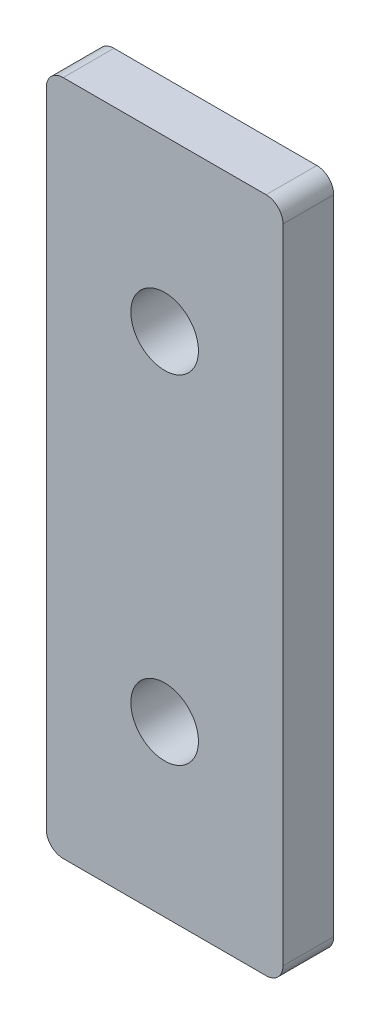
SolidWorks part; units mm, degrees
ref_plane "Front Plane" through (0, 0, 0) normal (0, 0, 1) x (1, 0, 0)
ref_plane "Top Plane" through (0, 0, 0) normal (0, 1, 0) x (1, 0, 0)
ref_plane "Right Plane" through (0, 0, 0) normal (1, 0, 0) x (0, 0, -1)
sketch "Sketch1" plane through (0, 0, 0) normal (0, 0, 1) x (1, 0, 0)
  line L0 (7, 40) -> (7, 0) construction
  line L1 (0, 0) -> (14, 0)
  line L2 (0, 0) -> (0, 40)
  line L3 (0, 40) -> (14, 40)
  line L4 (14, 0) -> (14, 40)
  circle A0 centre (7, 10) radius 2
  circle A1 centre (7, 30) radius 2
  dimension "D2" = 4
  dimension "D1" = 20
  dimension "D3" = 10
  dimension "D4" = 10
  dimension "D5" = 7
  dimension "D6" = 7
extrude "Boss-Extrude1" add sketch "Sketch1" along normal blind 3
fillet "Fillet1" radius 1 4 edges at (14, 0, 1.5) (0, 0, 1.5) (0, 40, 1.5) (14, 40, 1.5)
